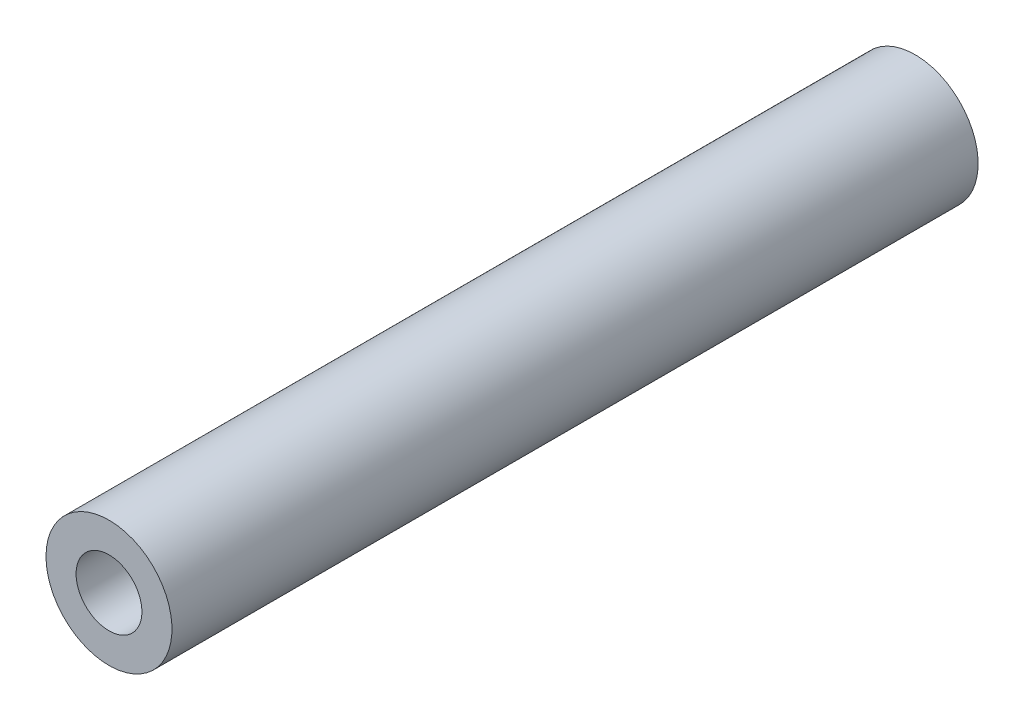
SolidWorks part; units mm, degrees
ref_plane "Front Plane" through (0, 0, 0) normal (0, 0, 1) x (1, 0, 0)
ref_plane "Top Plane" through (0, 0, 0) normal (0, 1, 0) x (1, 0, 0)
ref_plane "Right Plane" through (0, 0, 0) normal (1, 0, 0) x (0, 0, -1)
sketch "Sketch1" plane through (0, 0, 0) normal (0, 0, 1) x (1, 0, 0)
  circle A0 centre (0, 0) radius 4.7625
  circle A1 centre (0, 0) radius 2.4892
  dimension "D1" = 4.9784
  dimension "D2" = 9.525
extrude "Boss-Extrude1" add sketch "Sketch1" along normal mid plane 60.96
